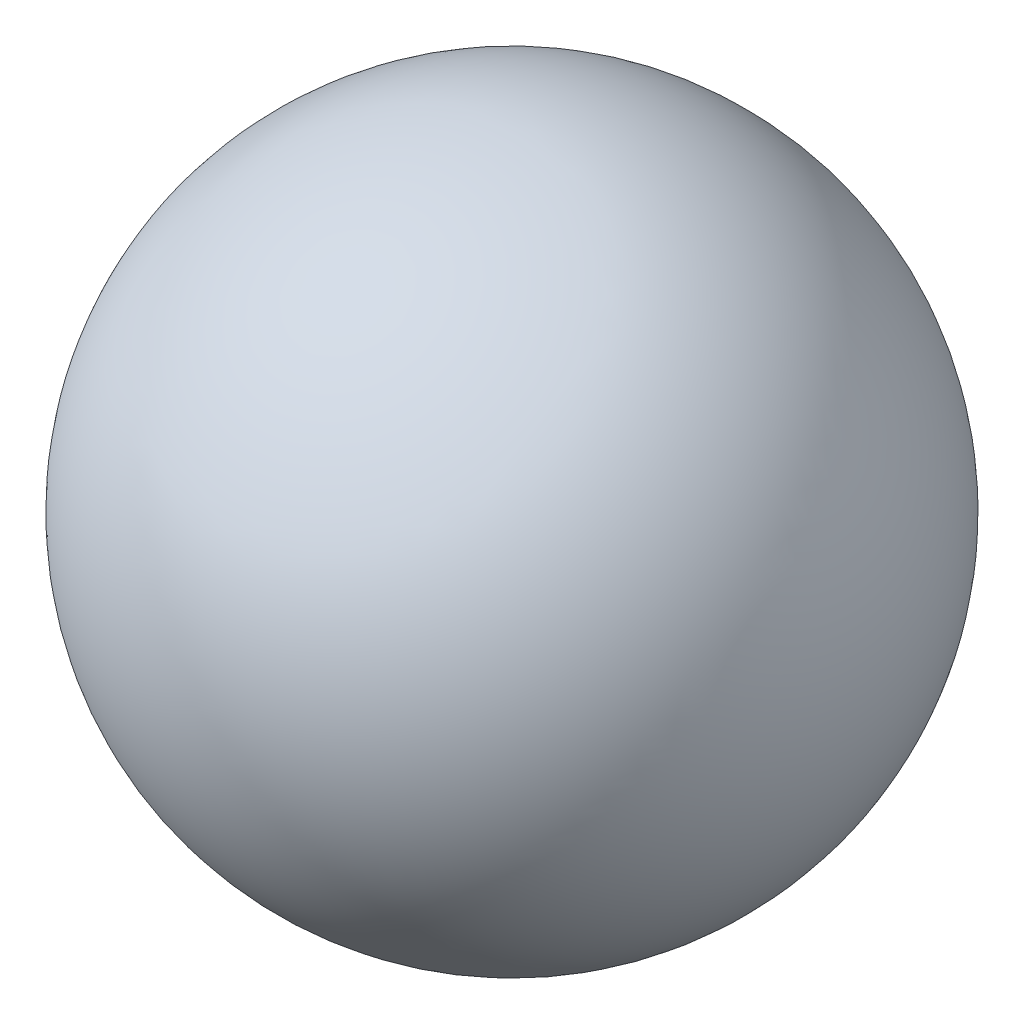
SolidWorks part; units mm, degrees
ref_plane "Front Plane" through (0, 0, 0) normal (0, 0, 1) x (1, 0, 0)
ref_plane "Top Plane" through (0, 0, 0) normal (0, 1, 0) x (1, 0, 0)
ref_plane "Right Plane" through (0, 0, 0) normal (1, 0, 0) x (0, 0, -1)
sketch "Sketch1" plane through (0, 0, 0) normal (0, 0, 1) x (1, 0, 0)
  line L0 (-20.32, 0) -> (20.32, 0)
  arc A0 (20.32, 0) -> (-20.32, 0) centre (0, 0) ccw
  dimension "D1" = 40.64
revolve "Revolve1" add sketch "Sketch1" angle 360 about L0
